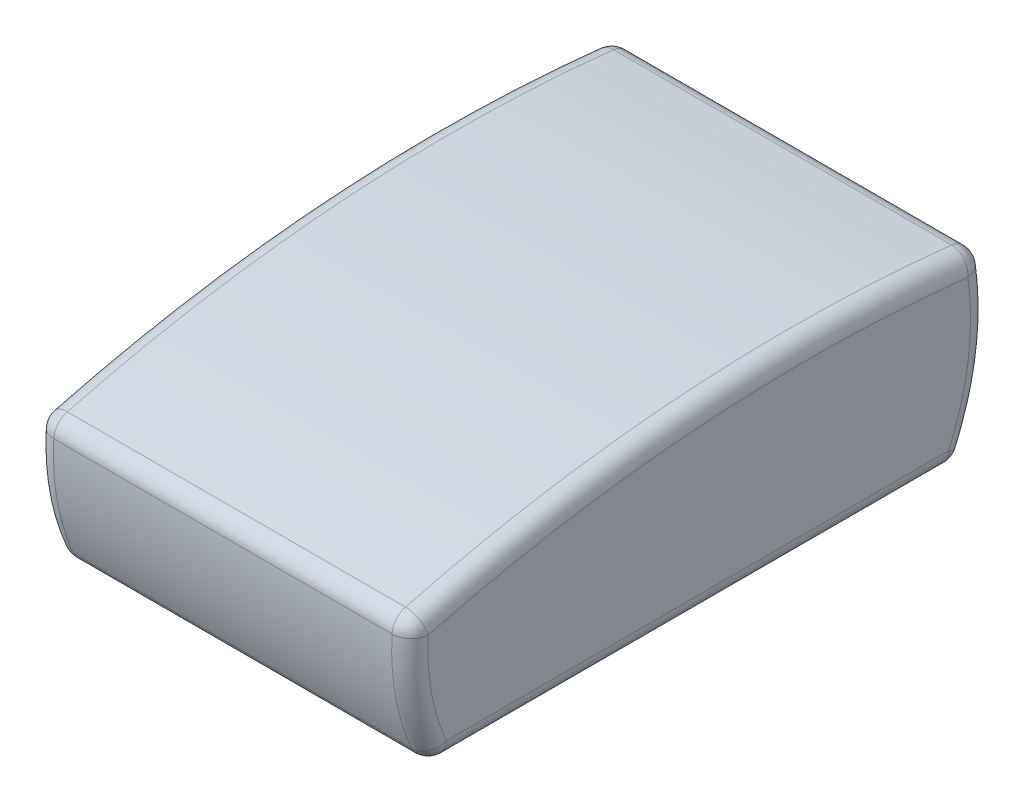
SolidWorks part; units mm, degrees
material "ABS"
ref_plane "Front Plane" through (0, 0, 0) normal (0, 0, 1) x (1, 0, 0)
ref_plane "Top Plane" through (0, 0, 0) normal (0, 1, 0) x (1, 0, 0)
ref_plane "Right Plane" through (0, 0, 0) normal (1, 0, 0) x (0, 0, -1)
sketch "Sketch1" plane through (0, 0, 0) normal (1, 0, 0) x (0, 0, -1)
  line L0 (-43.5, 0) -> (43.5, 0)
  line L1 (-43.5, 0) -> (-47.3792, 22) construction
  line L2 (-47.3792, 22) -> (47.3626, 29) construction
  line L3 (47.3626, 29) -> (43.5, 0) construction
  arc A0 (-43.5, 0) -> (-47.3792, 22) centre (-7.6143, 17.6696) cw
  arc A1 (43.5, 0) -> (47.3626, 29) centre (3.2477, 20.1185) ccw
  arc A2 (-47.3792, 22) -> (47.3626, 29) centre (18.0772, -219.2788) cw
  point P8 (0, 0)
  point P9 (0, 0)
  dimension "D4" = 40
  dimension "D7" = 250
  dimension "D8" = 45
  dimension "D1" = 87
  dimension "D2" = 22
  dimension "D3" = 29
  dimension "D5" = 95
  dimension "D6" = 100
extrude "Boss-Extrude1" add sketch "Sketch1" along normal blind 62
fillet "Fillet1" radius 3 12 edges at (31, 0, -43.5) (0, 0, 0) (31, 0, 43.5) (62, 0, 0) (31, 29, -47.3626) (0, 14.1773, -47.8538) (62, 14.1773, -47.8538) (62, 10.7237, 47.0066) (0, 10.7237, 47.0066) (0, 30.0416, 0.3439) (62, 30.0416, 0.3439) (31, 22, 47.3792)
sketch "Sketch2" plane through (0, 0, 0) normal (0, -1, 0) x (1, 0, 0)
  line L0 (31, 41.582) -> (31, -41.6008) construction
  line L1 (59, 41.582) -> (3, 41.582) construction
  line L2 (3, -41.6008) -> (59, -41.6008) construction
  line L3 (11, 5.6143) -> (31, 5.6143) construction
  line L4 (31, 5.6143) -> (51, 5.6143) construction
  line L5 (11, 5.6143) -> (11, -2.4429) construction
  line L6 (11, -2.4429) -> (51, -2.4429) construction
  line L7 (51, -2.4429) -> (51, 5.6143) construction
  line L8 (59, 47.6143) -> (3, 47.6143) construction
  line L9 (59, 47.5571) -> (3, 47.5571) construction
  line L10 (7, 5.6143) -> (7, -2.4429)
  line L11 (7, -2.4429) -> (15, -2.4429)
  line L12 (15, -2.4429) -> (15, 5.6143)
  line L13 (47, -2.4429) -> (47, 5.6143)
  line L14 (55, 5.6143) -> (55, -2.4429)
  circle A0 centre (11, 5.6143) radius 4
  circle A1 centre (51, 5.6143) radius 4
  circle A2 centre (11, -2.4429) radius 4
  circle A3 centre (51, -2.4429) radius 4
  dimension "D1" = 20
  dimension "D2" = 8
  dimension "D3" = 42
  dimension "D4" = 50
extrude "Cut-Extrude1" cut sketch "Sketch2" against normal blind 20 contours A0 | A2 L12 A0 L10 | L11 A2 | L11 A2 | A3 | A3 L14 A1 L13 | A1
